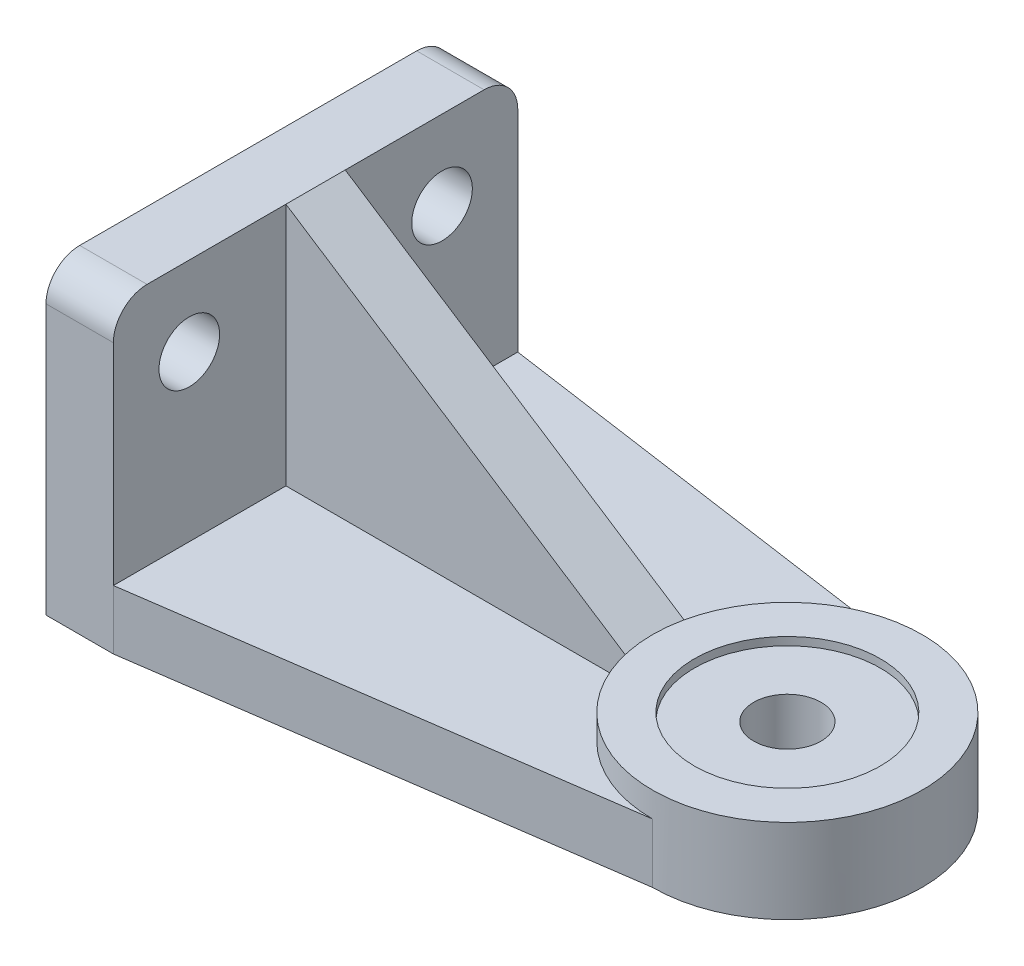
SolidWorks part; units mm, degrees
material "7075-T6 (SN)"
ref_plane "Front" through (0, 0, 0) normal (0, 0, 1) x (1, 0, 0)
ref_plane "Top" through (0, 0, 0) normal (0, 1, 0) x (1, 0, 0)
ref_plane "Right" through (0, 0, 0) normal (1, 0, 0) x (0, 0, -1)
sketch "Sketch1" plane through (0, 0, 0) normal (0, 1, 0) x (1, 0, 0)
  circle A0 centre (0, 0) radius 25.4
  dimension "D1" = 50.8
extrude "Boss-Extrude1" add sketch "Sketch1" along normal blind 15.875
sketch "Sketch2" plane through (0, 0, 0) normal (0, 1, 0) x (1, 0, 0)
  line L0 (0, 0) -> (-88.9, 0) construction
  line L1 (-88.9, 38.1) -> (-88.9, -38.1)
  line L2 (-88.9, 38.1) -> (0, 25.4)
  line L3 (-88.9, -38.1) -> (0, -25.4)
  circle A0 centre (0, 0) radius 25.4 construction
  arc A1 (0, 25.4) -> (0, -25.4) centre (0, 0) ccw
  point P5 (-88.9, 0)
extrude "Boss-Extrude2" add sketch "Sketch2" along normal blind 11.176
sketch "Sketch3" plane through (0, 0, 0) normal (0, 1, 0) x (1, 0, 0)
  line L1 (-88.9, 38.1) -> (-101.6, 38.1)
  line L2 (-88.9, 38.1) -> (-88.9, -38.1)
  line L3 (-88.9, -38.1) -> (-101.6, -38.1)
  line L4 (-101.6, 38.1) -> (-101.6, -38.1)
  dimension "D1" = 12.7
  dimension "D2" = 76.2
extrude "Boss-Extrude3" add sketch "Sketch3" along normal blind 57.15
ref_plane "Plane1" through (0, 11.176, 0) normal (0, 1, 0) x (1, 0, 0)
ref_plane "Plane2" through (0, 0, 0) normal (0, 0, 1) x (1, 0, 0)
hole_wizard "CBORE for 3/8 Binding Head Machine Screw1" positions "3DSketch2" profile "Sketch9" counterbore size "3/8" standard "ANSI Inch" end condition through all
sketch3d "3DSketch2"
  line L0 (0, 15.875, 0) -> (0, 11.176, 0) construction
  point P0 (0, 15.875, 0)
sketch "Sketch9" plane through (0, 15.875, 0) normal (1, 0, 0) x (0, 0, 1)
  line L0 (0, 0) -> (0, 15.875)
  line L1 (0, 15.875) -> (6.35, 15.875)
  line L3 (6.35, 15.875) -> (6.35, 1.524)
  line L4 (6.35, 1.524) -> (17.526, 1.524)
  line L5 (17.526, 1.524) -> (17.526, 0)
  line L7 (17.526, 0) -> (0, 0)
  line L11 (0, -6.35) -> (0, 107.95) construction
  dimension "Thru Hole Dia." = 12.7
  dimension "Thru Hole Depth" = 15.875
  dimension "C'Bore Dia." = 35.052
  dimension "C'Bore Depth" = 1.524
sketch "Sketch10" plane through (0, 0, 0) normal (0, 0, 1) x (1, 0, 0)
  line L0 (-88.9, 57.15) -> (-25.4, 15.875)
  line L1 (-25.4, 15.875) -> (-22.86, 14.224)
  line L2 (-22.86, 14.224) -> (-22.86, 11.176)
  line L3 (-88.9, 11.176) -> (0, 11.176) construction
  line L4 (-22.86, 11.176) -> (-88.9, 11.176)
  line L5 (-88.9, 11.176) -> (-88.9, 57.15)
  line L6 (-25.4, 15.875) -> (-25.4, 11.176) construction
  dimension "D1" = 2.54
extrude "Boss-Extrude7" add sketch "Sketch10" along normal mid plane 11.176
hole_wizard "25/64 (0.45) Diameter Hole1" positions "3DSketch3" profile "Sketch11" hole size "25/64" standard "ANSI Inch" end condition through all
sketch3d "3DSketch3"
  line L0 (-88.9, 57.15, 38.1) -> (-88.9, 57.15, 5.588) construction
  line L1 (-88.9, 57.15, -5.588) -> (-88.9, 57.15, -38.1) construction
  line L2 (-88.9, 57.15, 38.1) -> (-88.9, 11.176, 38.1) construction
  point P0 (-88.9, 42.164, 23.7998)
  point P2 (-88.9, 42.164, -23.8252)
  dimension "D1" = 14.986
  dimension "D2" = 14.986
  dimension "D3" = 14.3002
  dimension "D4" = 47.625
sketch "Sketch11" plane through (-88.9, 42.164, 23.7998) normal (0, 1, 0) x (0, 0, -1)
  line L0 (0, 0) -> (0, 12.7)
  line L1 (0, 12.7) -> (5.715, 12.7)
  line L2 (5.715, 12.7) -> (5.715, 0)
  line L5 (5.715, 0) -> (0, 0)
  line L11 (0, -6.35) -> (0, 107.95) construction
  dimension "Thru Hole Dia." = 11.43
  dimension "Thru Hole Depth" = 12.7
fillet "Fillet1" radius 6.35 2 edges at (-95.25, 57.15, -38.1) (-95.25, 57.15, 38.1)
